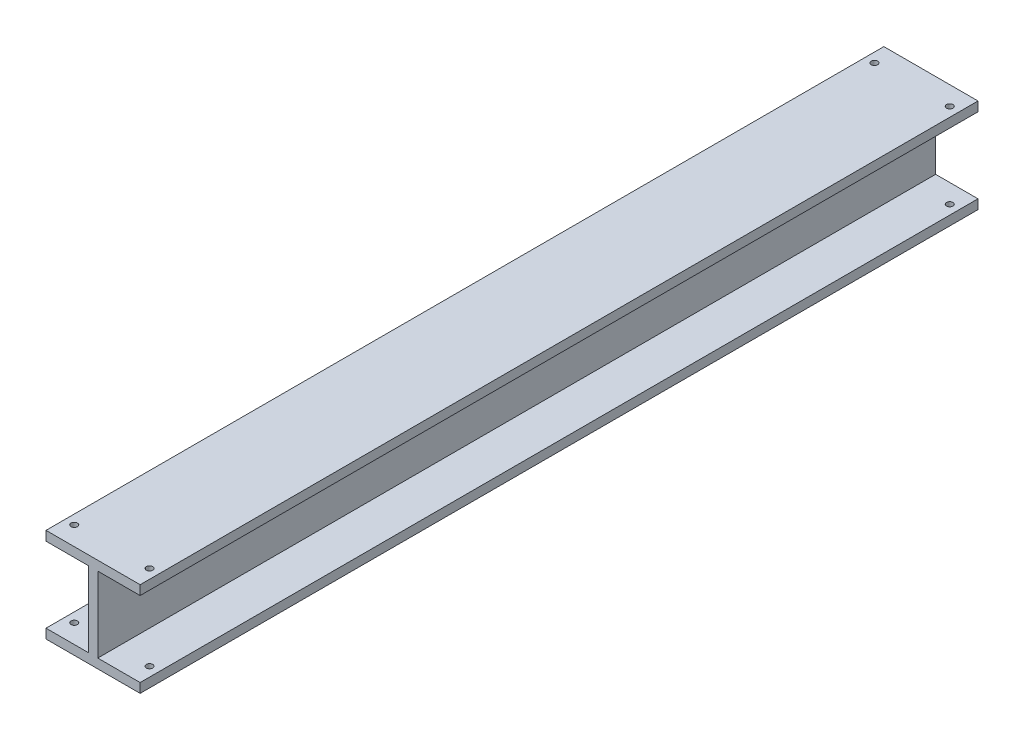
SolidWorks part; units mm, degrees
ref_plane "Ebene vorne" through (0, 0, 0) normal (0, 0, 1) x (1, 0, 0)
ref_plane "Ebene oben" through (0, 0, 0) normal (0, 1, 0) x (1, 0, 0)
ref_plane "Ebene rechts" through (0, 0, 0) normal (1, 0, 0) x (0, 0, -1)
sketch "Skizze1" plane through (0, 0, 0) normal (0, 0, 1) x (1, 0, 0)
  line L0 (-50, 50) -> (50, 50)
  line L1 (50, 50) -> (50, 40)
  line L2 (50, 40) -> (5, 40)
  line L3 (5, 40) -> (5, -40)
  line L4 (5, -40) -> (50, -40)
  line L5 (50, -40) -> (50, -50)
  line L6 (50, -50) -> (-50, -50)
  line L7 (-50, -50) -> (-50, -40)
  line L8 (-50, -40) -> (-5, -40)
  line L9 (-5, -40) -> (-5, 40)
  line L10 (-5, 40) -> (-50, 40)
  line L11 (-50, 40) -> (-50, 50)
  line L12 (0, 0) -> (0, 43.1345) construction
  line L13 (0, 0) -> (53.0053, 0) construction
  dimension "D1" = 10
  dimension "D2" = 10
  dimension "D3" = 100
  dimension "D4" = 100
extrude "Aufsatz-Linear austragen1" add sketch "Skizze1" along normal blind 890
sketch "Skizze2" plane through (0, 50, 0) normal (0, 1, 0) x (1, 0, 0)
  line L0 (0, -890) -> (0, -848.3137) construction
  line L1 (50, -890) -> (-50, -890) construction
  line L2 (50, -890) -> (50, 0) construction
  line L3 (-50, -890) -> (-50, 0) construction
  circle A0 centre (40, -870) radius 3.4
  circle A1 centre (-40, -870) radius 3.4
  dimension "D1" = 10
  dimension "D2" = 6.8
  dimension "D3" = 20
extrude "Schnitt-Linear austragen1" cut sketch "Skizze2" against normal through all
ref_plane "Ebene1" through (0, 0, 445) normal (0, 0, 1) x (1, 0, 0)
mirror "Spiegeln1" about plane through (0, 0, 445) normal (0, 0, 1) of "Schnitt-Linear austragen1"
